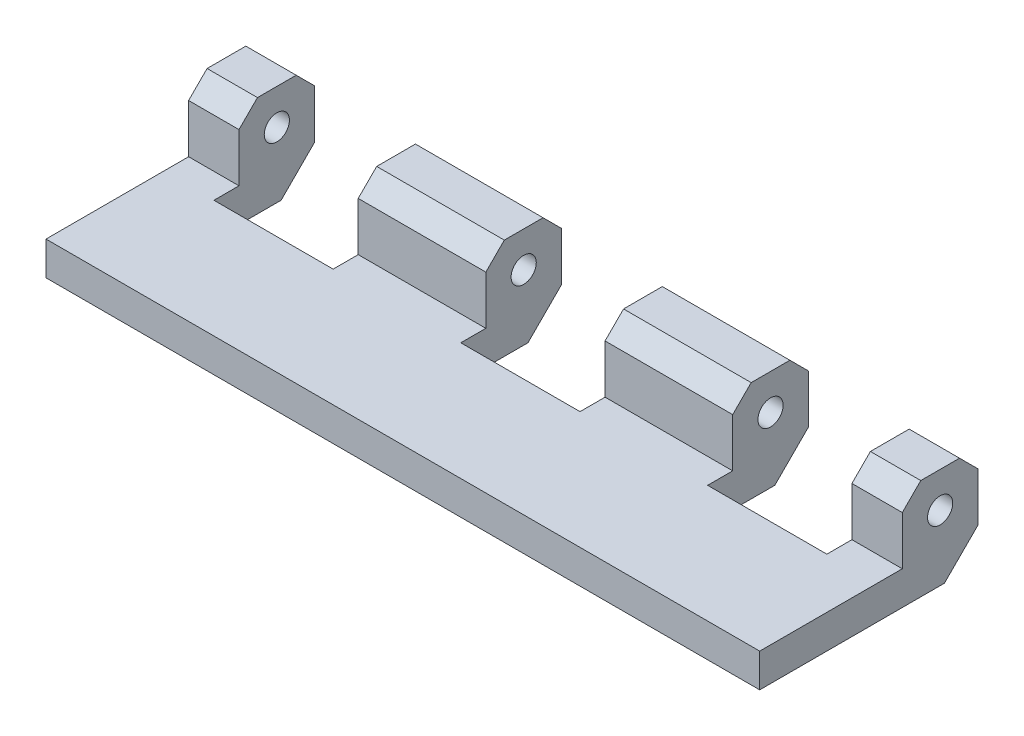
SolidWorks part; units mm, degrees
ref_plane "Спереди" through (0, 0, 0) normal (0, 0, 1) x (1, 0, 0)
ref_plane "Сверху" through (0, 0, 0) normal (0, 1, 0) x (1, 0, 0)
ref_plane "Справа" through (0, 0, 0) normal (1, 0, 0) x (0, 0, -1)
sketch "Эскиз1" plane through (0, 0, 0) normal (0, 1, 0) x (1, 0, 0)
  line L1 (-9, 0) -> (76, 0)
  line L2 (-9, 0) -> (-9, -26)
  line L3 (-9, -26) -> (76, -26)
  line L4 (76, 0) -> (76, -26)
extrude "Вытянуть1" add sketch "Эскиз1" along normal blind 12
sketch "Эскиз2" plane through (76, 0, 0) normal (1, 0, 0) x (0, 0, -1)
  line L0 (4.8026, 4) -> (-2.9217, 4) construction
  line L3 (-28.123, 13.0177) -> (-9.0163, 13.0177)
  line L4 (-28.123, 13.0177) -> (-28.123, 4)
  line L5 (-28.123, 4) -> (-9.0163, 4)
  line L6 (-9.0163, 13.0177) -> (-9.0163, 4)
  line L7 (-26, 0) -> (0, 0) construction
  dimension "D1" = 4
extrude "Вырез-Вытянуть1" cut sketch "Эскиз2" against normal through all
chamfer "Фаска1" distance 2.2 angle 45 2 edges at (33.5, 12, 0) (33.5, 12, 9.0163)
chamfer "Фаска2" distance 4 angle 45 1 edges at (33.5, 0, 0)
sketch "Эскиз3" plane through (76, 0, 0) normal (1, 0, 0) x (0, 0, -1)
  line L0 (-4.5081, 12) -> (-4.5081, 13.7201) construction
  circle A0 centre (-4.5081, 7.7771) radius 1.5
extrude "Вырез-Вытянуть2" cut sketch "Эскиз3" against normal through all
sketch "Эскиз4" plane through (0, 12, 0) normal (0, 1, 0) x (1, 0, 0)
  line L0 (62.9, -6) -> (62.9, -29.2492) construction
  line L1 (33.5, -2.2) -> (33.5, 33.0348) construction
  line L3 (11.2, -12) -> (-3, -12)
  line L4 (-3, -12) -> (-3, 0)
  line L5 (11.2, 0) -> (-3, 0)
  line L6 (55.8, -12) -> (70, -12)
  line L7 (55.8, -12) -> (55.8, 0)
  line L8 (11.2, -12) -> (11.2, 0)
  line L9 (55.8, 0) -> (70, 0)
  line L10 (70, -12) -> (70, 0)
  line L11 (55.8, -12) -> (70, 0) construction
  line L12 (55.8, 0) -> (70, -12) construction
  line L13 (-3, -6) -> (-41.2943, -6) construction
  line L14 (-9, 0) -> (76, 0) construction
  line L15 (26.4, -12) -> (40.6, -12)
  line L16 (26.4, -12) -> (26.4, 0)
  line L17 (26.4, 0) -> (40.6, 0)
  line L18 (40.6, -12) -> (40.6, 0)
  line L19 (26.4, -12) -> (40.6, 0) construction
  line L20 (26.4, 0) -> (40.6, -12) construction
  point P6 (62.9, -6)
  point P14 (33.5, -6)
extrude "Вырез-Вытянуть3" cut sketch "Эскиз4" against normal through all
